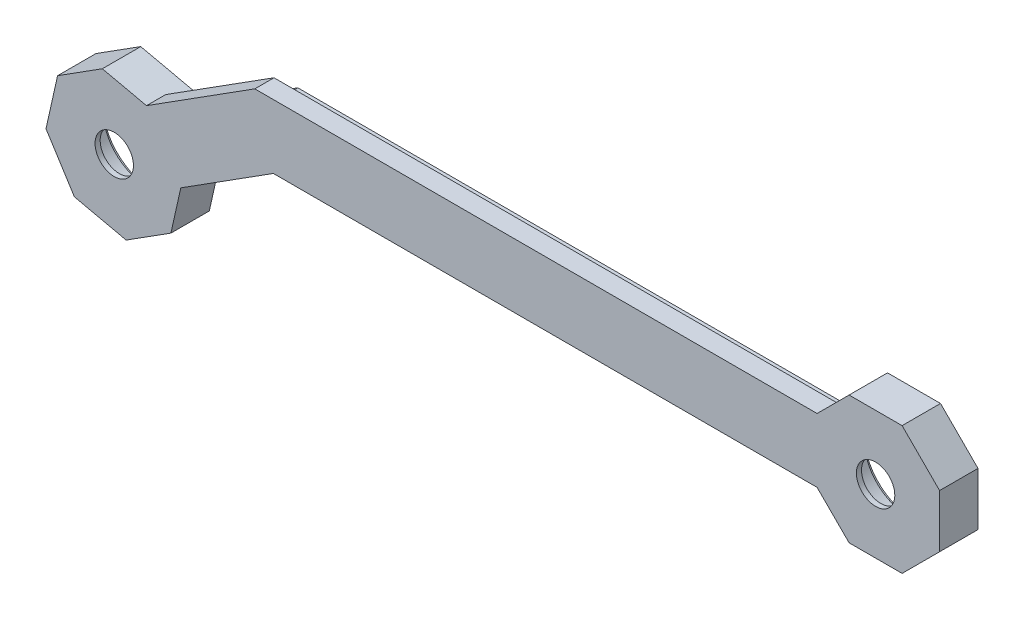
SolidWorks part; units mm, degrees
material "AISI 1020"
ref_plane "Front Plane" through (0, 0, 0) normal (0, 0, 1) x (1, 0, 0)
ref_plane "Top Plane" through (0, 0, 0) normal (0, 1, 0) x (1, 0, 0)
ref_plane "Right Plane" through (0, 0, 0) normal (1, 0, 0) x (0, 0, -1)
sketch "Sketch1" plane through (0, 0, 0) normal (0, 0, 1) x (1, 0, 0)
  line L0 (0, 0) -> (-95.55, 0) construction
  line L1 (-95.55, 0) -> (-118.9664, -14.8548) construction
  line L2 (-108.5682, -14.1796) -> (-94.0978, -5)
  line L3 (4.1421, 10) -> (-4.1421, 10)
  line L4 (-4.1421, 10) -> (-10, 4.1421)
  line L6 (-10, -4.1421) -> (-4.1421, -10)
  line L7 (-4.1421, -10) -> (4.1421, -10)
  line L8 (4.1421, -10) -> (10, -4.1421)
  line L9 (10, -4.1421) -> (10, 4.1421)
  line L10 (10, 4.1421) -> (4.1421, 10)
  line L11 (-127.8209, -8.6294) -> (-129.6295, -16.7139)
  line L12 (-129.6295, -16.7139) -> (-125.1918, -23.7093)
  line L13 (-125.1918, -23.7093) -> (-117.1073, -25.5178)
  line L14 (-117.1073, -25.5178) -> (-110.1119, -21.0801)
  line L15 (-110.1119, -21.0801) -> (-108.3033, -12.9957)
  line L17 (-112.7411, -6.0003) -> (-120.8255, -4.1917)
  line L18 (-120.8255, -4.1917) -> (-127.8209, -8.6294)
  line L19 (-94.0978, -5) -> (-9.1421, -5)
  line L20 (-97.0022, 5) -> (-9.1421, 5)
  line L21 (-113.925, -5.7354) -> (-97.0022, 5)
  line L22 (-94.0978, -5) -> (-97.0022, 5)
  line L23 (-120.8255, -4.1917) -> (-110.4747, -6.5073)
  line L24 (-4.1421, 10) -> (-11.6421, 2.5)
  line L25 (-4.1421, -10) -> (-11.6421, -2.5)
  line L26 (-110.1119, -21.0801) -> (-107.7963, -10.7294)
  line L27 (-11.6421, 2.5) -> (-96.2761, 2.5)
  line L28 (-96.2761, 2.5) -> (-110.4747, -6.5073)
  line L29 (-94.8239, -2.5) -> (-107.7963, -10.7294)
  line L30 (-11.6421, -2.5) -> (-94.8239, -2.5)
  line L31 (-94.8239, -2.5) -> (-107.7963, -10.7294)
  line L32 (-108.3033, -12.9957) -> (-110.5222, -9.498) [skipped]
  line L33 (-10, 0) -> (-10, -4.1421) [skipped]
  arc A0 (-7.0711, -7.0711) -> (-7.0711, 7.0711) centre (0, 0) ccw construction
  arc A1 (-116.7833, -5.096) -> (-109.2076, -17.0379) centre (-118.9664, -14.8548) ccw construction
  circle A2 centre (-118.9664, -14.8548) radius 3
  circle A3 centre (-0.8766, 0) radius 3
  dimension "D1" = 95.55
  dimension "D2" = 20
  dimension "D3" = 20
  dimension "D4" = 147.61
  dimension "D5" = 10
  dimension "D6" = 26.75
  dimension "D7" = 10
  dimension "D8" = 5
extrude "Boss-Extrude1" add sketch "Sketch1" against normal blind 6 contours L29 L22 L28 L23 L17 L18 L11 L12 L13 L14 L15 L26 A2 | L30 L25 L6 L7 L8 L9 L10 L3 L4 L24 L27 L22 A3
sketch "Sketch2" plane through (0, 0, 0) normal (0, 0, 1) x (1, 0, 0)
  line L0 (-113.925, -5.7354) -> (-110.4747, -6.5073)
  line L1 (-110.4747, -6.5073) -> (-96.2761, 2.5)
  line L2 (-96.2761, 2.5) -> (-11.6421, 2.5)
  line L3 (-11.6421, 2.5) -> (-9.1421, 5)
  line L4 (-9.1421, 5) -> (-97.0022, 5)
  line L5 (-97.0022, 5) -> (-113.925, -5.7354)
  line L6 (-108.5682, -14.1796) -> (-107.7963, -10.7294)
  line L7 (-107.7963, -10.7294) -> (-94.8239, -2.5)
  line L8 (-94.8239, -2.5) -> (-11.6421, -2.5)
  line L9 (-11.6421, -2.5) -> (-9.1421, -5)
  line L10 (-9.1421, -5) -> (-94.0978, -5)
  line L11 (-94.0978, -5) -> (-108.5682, -14.1796)
extrude "Boss-Extrude2" add sketch "Sketch2" against normal blind 3
sketch "Sketch3" plane through (0, 0, -6) normal (0, 0, -1) x (-1, 0, 0)
  circle A0 centre (0, 0) radius 7.85
  circle A1 centre (118.9664, -14.8548) radius 7.85
extrude "Cut-Extrude1" cut sketch "Sketch3" against normal blind 1
sketch "Sketch4" plane through (0, 0, -6) normal (0, 0, -1) x (-1, 0, 0)
  circle A0 centre (0, 0) radius 6.75
  circle A1 centre (118.9664, -14.8548) radius 6.75
extrude "Cut-Extrude2" cut sketch "Sketch4" against normal blind 5.2
sketch "Sketch5" plane through (0, 0, 0) normal (0, 0, 1) x (1, 0, 0)
  line L1 (-6.0261, -3.3388) -> (4.2729, -3.3388)
  line L2 (-6.0261, -3.3388) -> (-6.0261, 3.3388)
  line L3 (-6.0261, 3.3388) -> (4.2729, 3.3388)
  line L4 (4.2729, -3.3388) -> (4.2729, 3.3388)
  line L5 (-6.0261, -3.3388) -> (4.2729, 3.3388) construction
  line L6 (-6.0261, 3.3388) -> (4.2729, -3.3388) construction
  point P0 (-0.8766, 0)
extrude "Boss-Extrude3" add sketch "Sketch5" against normal blind 0.8
sketch "Sketch6" plane through (0, 0, 0) normal (0, 0, 1) x (1, 0, 0)
  circle A0 centre (0, 0) radius 3
extrude "Cut-Extrude3" cut sketch "Sketch6" against normal blind 0.8
equation "\"A\"= 100"
equation "\"B\"= 100"
equation "\"C\"= 100"
equation "\"D\"= 100"
equation "\"E\"= 100"
